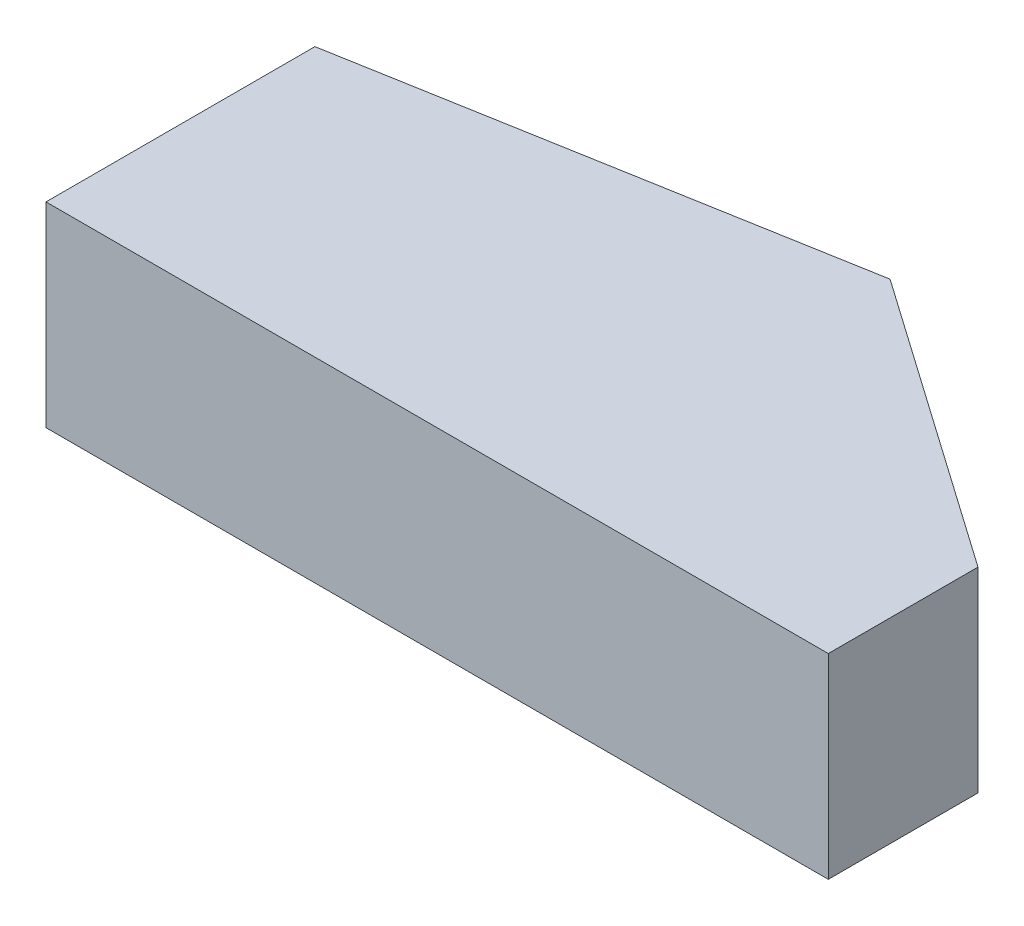
SolidWorks part; units mm, degrees
ref_plane "Front Plane" through (0, 0, 0) normal (0, 0, 1) x (1, 0, 0)
ref_plane "Top Plane" through (0, 0, 0) normal (0, 1, 0) x (1, 0, 0)
ref_plane "Right Plane" through (0, 0, 0) normal (1, 0, 0) x (0, 0, -1)
sketch "Croquis2" plane through (0, 0, 0) normal (0, 1, 0) x (1, 0, 0)
  line L0 (0, 0) -> (101.6, 0)
  line L1 (101.6, 0) -> (101.6, 19.4439)
  line L2 (101.6, 19.4439) -> (63.5, 46.1218)
  line L3 (63.5, 46.1218) -> (0, 34.925)
  line L4 (0, 34.925) -> (0, 0)
  dimension "D1" = 101.6
  dimension "D2" = 34.925
  dimension "D3" = 63.5
  dimension "D4" = 100
  dimension "D5" = 135
extrude "Saliente-Extruir1" add sketch "Croquis2" along normal blind 25.4
